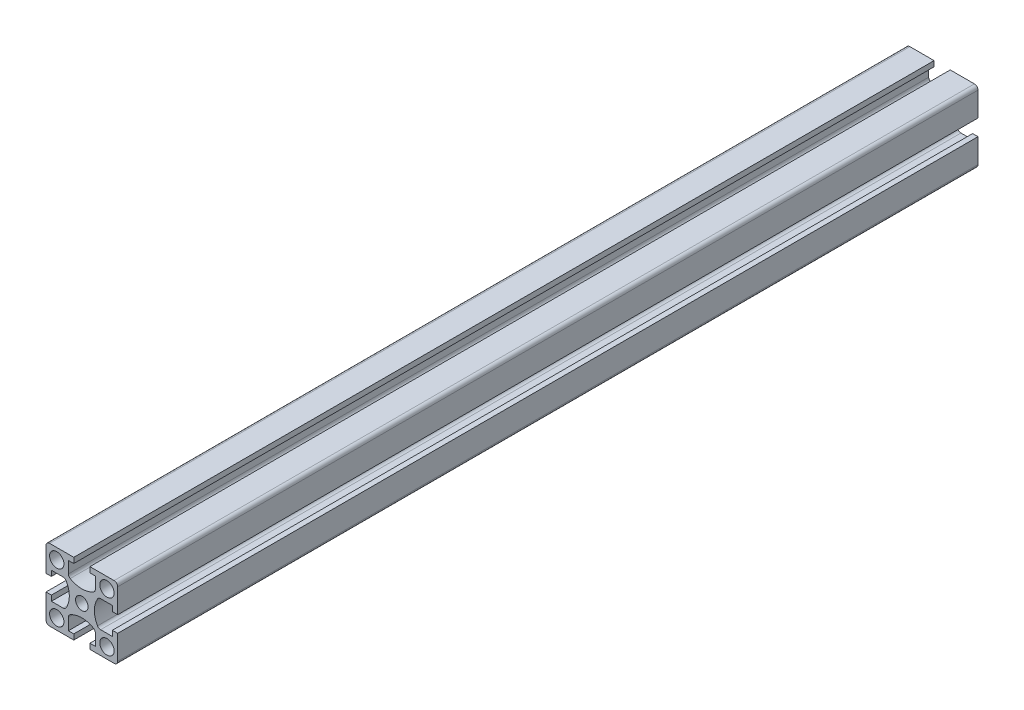
SolidWorks part; units mm, degrees
ref_plane "Front Plane" through (0, 0, 0) normal (0, 0, 1) x (1, 0, 0)
ref_plane "Top Plane" through (0, 0, 0) normal (0, 1, 0) x (1, 0, 0)
ref_plane "Right Plane" through (0, 0, 0) normal (1, 0, 0) x (0, 0, -1)
sketch "Sketch1" plane through (0, 0, 0) normal (0, 0, 1) x (1, 0, 0)
  line L64 (-25, 22.5) -> (-25, 5.625)
  line L65 (-25, 5.625) -> (-21.25, 5.625)
  line L66 (-21.25, 5.625) -> (-21.25, 9.375)
  line L67 (-21.25, 9.375) -> (-13.0922, 9.375)
  line L68 (-13.0922, -9.375) -> (-21.25, -9.375)
  line L69 (-21.25, -9.375) -> (-21.25, -5.625)
  line L70 (-21.25, -5.625) -> (-25, -5.625)
  line L71 (-25, -5.625) -> (-25, -22.5)
  line L72 (-22.5, -25) -> (-5.625, -25)
  line L73 (-5.625, -25) -> (-5.625, -21.25)
  line L74 (-5.625, -21.25) -> (-9.375, -21.25)
  line L75 (-9.375, -21.25) -> (-9.375, -13.0922)
  line L76 (9.375, -13.0922) -> (9.375, -21.25)
  line L77 (9.375, -21.25) -> (5.625, -21.25)
  line L78 (5.625, -21.25) -> (5.625, -25)
  line L79 (5.625, -25) -> (22.5, -25)
  line L80 (25, -22.5) -> (25, -5.625)
  line L81 (25, -5.625) -> (21.25, -5.625)
  line L82 (21.25, -5.625) -> (21.25, -9.375)
  line L83 (21.25, -9.375) -> (13.0922, -9.375)
  line L84 (13.0922, 9.375) -> (21.25, 9.375)
  line L85 (21.25, 9.375) -> (21.25, 5.625)
  line L86 (21.25, 5.625) -> (25, 5.625)
  line L87 (25, 5.625) -> (25, 22.5)
  line L88 (22.5, 25) -> (5.625, 25)
  line L89 (5.625, 25) -> (5.625, 21.25)
  line L90 (5.625, 21.25) -> (9.375, 21.25)
  line L91 (9.375, 21.25) -> (9.375, 13.0922)
  line L92 (-9.375, 13.0922) -> (-9.375, 21.25)
  line L93 (-9.375, 21.25) -> (-5.625, 21.25)
  line L94 (-5.625, 21.25) -> (-5.625, 25)
  line L95 (-5.625, 25) -> (-22.5, 25)
  circle A5 centre (-17.5, -17.5) radius 5
  circle A6 centre (17.5, -17.5) radius 5
  circle A7 centre (17.5, 17.5) radius 5
  circle A8 centre (0, 0) radius 4.375
  circle A9 centre (-17.5, 17.5) radius 5
  arc A32 (-22.5, 25) -> (-25, 22.5) centre (-22.5, 22.5) ccw
  arc A33 (-10.9271, 8.125) -> (-13.0922, 9.375) centre (-13.0922, 6.875) ccw
  arc A34 (-10.9271, -8.125) -> (-10.9271, 8.125) centre (-25, 0) ccw
  arc A35 (-13.0922, -9.375) -> (-10.9271, -8.125) centre (-13.0922, -6.875) ccw
  arc A36 (-25, -22.5) -> (-22.5, -25) centre (-22.5, -22.5) ccw
  arc A37 (-8.125, -10.9271) -> (-9.375, -13.0922) centre (-6.875, -13.0922) ccw
  arc A38 (8.125, -10.9271) -> (-8.125, -10.9271) centre (0, -25) ccw
  arc A39 (9.375, -13.0922) -> (8.125, -10.9271) centre (6.875, -13.0922) ccw
  arc A40 (22.5, -25) -> (25, -22.5) centre (22.5, -22.5) ccw
  arc A41 (10.9271, -8.125) -> (13.0922, -9.375) centre (13.0922, -6.875) ccw
  arc A42 (10.9271, 8.125) -> (10.9271, -8.125) centre (25, 0) ccw
  arc A43 (13.0922, 9.375) -> (10.9271, 8.125) centre (13.0922, 6.875) ccw
  arc A44 (25, 22.5) -> (22.5, 25) centre (22.5, 22.5) ccw
  arc A45 (8.125, 10.9271) -> (9.375, 13.0922) centre (6.875, 13.0922) ccw
  arc A46 (-8.125, 10.9271) -> (8.125, 10.9271) centre (0, 25) ccw
  arc A47 (-9.375, 13.0922) -> (-8.125, 10.9271) centre (-6.875, 13.0922) ccw
  dimension "D3" = 10
  dimension "D4" = 8.75
  dimension "D8" = 16.25
  dimension "D9" = 2.5
  dimension "D15" = 16.25
  dimension "D1" = 50
  dimension "D2" = 50
  dimension "D5" = 19.375
  dimension "D6" = 19.375
  dimension "D7" = 3.75
  dimension "D10" = 8.1578
  dimension "D11" = 3.75
  dimension "D12" = 8.1578
  dimension "D13" = 3.75
  dimension "D14" = 3.75
extrude "Boss-Extrude1" add sketch "Sketch1" along normal blind 600
